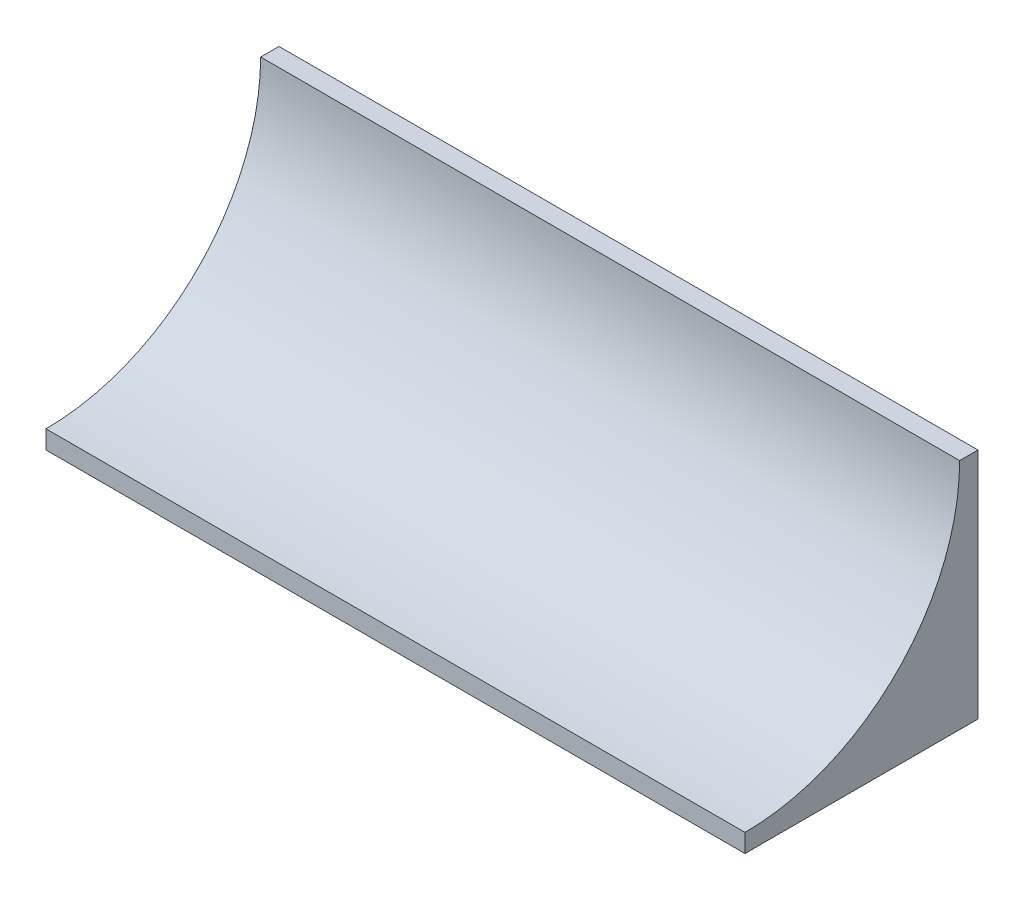
SolidWorks part; units mm, degrees
material "PET"
ref_plane "Alzado" through (0, 0, 0) normal (0, 0, 1) x (1, 0, 0)
ref_plane "Planta" through (0, 0, 0) normal (0, 1, 0) x (1, 0, 0)
ref_plane "Vista lateral" through (0, 0, 0) normal (1, 0, 0) x (0, 0, -1)
sketch "Sketch1" plane through (0, 0, 0) normal (1, 0, 0) x (0, 0, -1)
  line L1 (-25.4, -25.4) -> (25.4, -25.4)
  line L2 (-25.4, -25.4) -> (-25.4, 25.4)
  line L3 (-25.4, 25.4) -> (25.4, 25.4)
  line L4 (25.4, -25.4) -> (25.4, 25.4)
  line L5 (-25.4, -25.4) -> (25.4, 25.4) construction
  line L6 (-25.4, 25.4) -> (25.4, -25.4) construction
  point P0 (0, 0)
  dimension "D1" = 50.8
  dimension "D2" = 50.8
extrude "Boss-Extrude1" add sketch "Sketch1" along normal blind 76.2
sketch "Sketch2" plane through (76.2, 0, 0) normal (1, 0, 0) x (0, 0, -1)
  line L0 (0, -23.4) -> (0, -25.4)
  line L1 (23.4, 0) -> (25.4, 0)
  line L4 (25.4, -25.4) -> (25.4, 25.4)
  line L5 (25.4, 25.4) -> (-25.4, 25.4)
  line L6 (-25.4, 25.4) -> (-25.4, -25.4)
  line L7 (-25.4, -25.4) -> (25.4, -25.4)
  line L8 (25.4, -25.4) -> (25.4, 25.4)
  line L9 (25.4, 25.4) -> (-25.4, 25.4)
  line L10 (-25.4, 25.4) -> (-25.4, -25.4)
  line L11 (-25.4, -25.4) -> (25.4, -25.4)
  circle A0 centre (0, 0) radius 23.4
  line M6 (25.4, -25.4) -> (25.4, 25.4)
  line M7 (25.4, 25.4) -> (-25.4, 25.4)
  line M8 (-25.4, 25.4) -> (-25.4, -25.4)
  line M9 (-25.4, -25.4) -> (25.4, -25.4)
  dimension "D2" = 2
  dimension "D1" = 0
extrude "Cut-Extrude1" cut sketch "Sketch2" against normal up to surface (76.2 mm away) contours A0 L1 L0 M6 M7 M8 M9 | A0 L10
